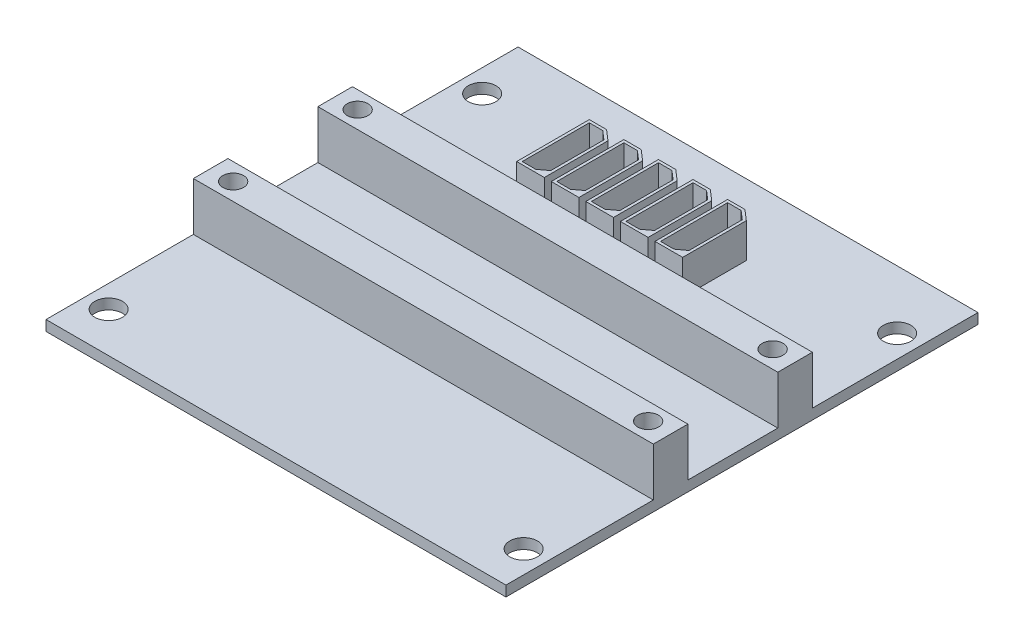
SolidWorks part; units mm, degrees
ref_plane "Front Plane" through (0, 0, 0) normal (0, 0, 1) x (1, 0, 0)
ref_plane "Top Plane" through (0, 0, 0) normal (0, 1, 0) x (1, 0, 0)
ref_plane "Right Plane" through (0, 0, 0) normal (1, 0, 0) x (0, 0, -1)
sketch "Sketch1" plane through (0, 0, 0) normal (0, 1, 0) x (1, 0, 0)
  line L1 (-33.25, 34.125) -> (33.25, 34.125)
  line L2 (-33.25, 34.125) -> (-33.25, -34.125)
  line L3 (-33.25, -34.125) -> (33.25, -34.125)
  line L4 (33.25, 34.125) -> (33.25, -34.125)
  line L5 (-33.25, 34.125) -> (33.25, -34.125) construction
  line L6 (-33.25, -34.125) -> (33.25, 34.125) construction
  point P0 (0, 0)
  dimension "D1" = 68.25
  dimension "D2" = 66.5
extrude "Boss-Extrude1" add sketch "Sketch1" along normal blind 1.5
sketch "Sketch3" plane through (0, 1.5, 0) normal (0, 1, 0) x (1, 0, 0)
  line L2 (0, 34.125) -> (0, -34.125) construction
  line L3 (33.25, 34.125) -> (-33.25, 34.125) construction
  line L4 (-33.25, -34.125) -> (33.25, -34.125) construction
  circle A0 centre (-30, -28.3176) radius 2
  circle A1 centre (30, -28.3176) radius 2
  circle A2 centre (30, 25.6824) radius 2
  circle A3 centre (-30, 25.6824) radius 2
  circle A4 centre (30, 7.6824) radius 1.5
  circle A5 centre (30, -10.3176) radius 1.5
  circle A6 centre (-30, -10.3176) radius 1.5
  circle A7 centre (-30, 7.6824) radius 1.5
  dimension "D7" = 4
  dimension "D8" = 4
  dimension "D9" = 4
  dimension "D10" = 4
  dimension "D14" = 3
  dimension "D15" = 3
  dimension "D1" = 60
  dimension "D2" = 30
  dimension "D3" = 30
  dimension "D4" = 54
  dimension "D5" = 54
  dimension "D6" = 30
  dimension "D11" = 18
  dimension "D12" = 18
  dimension "D13" = 18
extrude "Cut-Extrude1" cut sketch "Sketch3" against normal through all both and the other way through all
sketch "Sketch5" plane through (0, 1.5, 0) normal (0, 1, 0) x (1, 0, 0)
  line L5 (-14.0063, 25.1824) -> (-11.5063, 25.1824)
  line L6 (-11.5063, 25.1824) -> (-10.0063, 23.8824)
  line L8 (-10.0063, 23.8824) -> (-10.0063, 14.6824)
  line L9 (-10.0063, 14.6824) -> (-14.0063, 14.6824)
  line L10 (-14.0063, 14.6824) -> (-14.0063, 25.1824)
  line L11 (-10.4063, 23.6998) -> (-10.4063, 15.9998)
  line L12 (-11.6563, 15.0824) -> (-13.6063, 15.0824)
  line L13 (-13.6063, 15.0824) -> (-13.6063, 24.7824)
  line L14 (-13.6063, 24.7824) -> (-11.6555, 24.7824)
  line L15 (-11.6555, 24.7824) -> (-10.4063, 23.6998)
  line L16 (-10.4063, 15.9998) -> (-11.6563, 15.0824)
  line L17 (-10.4063, 23.6998) -> (-10.4063, 15.0824) construction
  line L18 (-10.4063, 15.0824) -> (-13.6063, 15.0824) construction
  line L19 (-9.0063, 25.1824) -> (-6.5063, 25.1824)
  line L20 (-6.5063, 25.1824) -> (-5.0063, 23.8824)
  line L21 (-5.0063, 23.8824) -> (-5.0063, 14.6824)
  line L22 (-5.0063, 14.6824) -> (-9.0063, 14.6824)
  line L23 (-9.0063, 14.6824) -> (-9.0063, 25.1824)
  line L24 (-5.4063, 23.6998) -> (-5.4063, 15.9998)
  line L25 (-6.6563, 15.0824) -> (-8.6063, 15.0824)
  line L26 (-8.6063, 15.0824) -> (-8.6063, 24.7824)
  line L27 (-8.6063, 24.7824) -> (-6.6555, 24.7824)
  line L28 (-6.6555, 24.7824) -> (-5.4063, 23.6998)
  line L29 (-5.4063, 15.9998) -> (-6.6563, 15.0824)
  line L30 (-4.0063, 25.1824) -> (-1.5063, 25.1824)
  line L31 (-1.5063, 25.1824) -> (-0.0063, 23.8824)
  line L32 (-0.0063, 23.8824) -> (-0.0063, 14.6824)
  line L33 (-0.0063, 14.6824) -> (-4.0063, 14.6824)
  line L34 (-4.0063, 14.6824) -> (-4.0063, 25.1824)
  line L35 (-0.4063, 23.6998) -> (-0.4063, 15.9998)
  line L36 (-1.6563, 15.0824) -> (-3.6063, 15.0824)
  line L37 (-3.6063, 15.0824) -> (-3.6063, 24.7824)
  line L38 (-3.6063, 24.7824) -> (-1.6555, 24.7824)
  line L39 (-1.6555, 24.7824) -> (-0.4063, 23.6998)
  line L40 (-0.4063, 15.9998) -> (-1.6563, 15.0824)
  line L41 (0.9937, 25.1824) -> (3.4937, 25.1824)
  line L42 (3.4937, 25.1824) -> (4.9937, 23.8824)
  line L43 (4.9937, 23.8824) -> (4.9937, 14.6824)
  line L44 (4.9937, 14.6824) -> (0.9937, 14.6824)
  line L45 (0.9937, 14.6824) -> (0.9937, 25.1824)
  line L46 (4.5937, 23.6998) -> (4.5937, 15.9998)
  line L47 (3.3437, 15.0824) -> (1.3937, 15.0824)
  line L48 (1.3937, 15.0824) -> (1.3937, 24.7824)
  line L49 (1.3937, 24.7824) -> (3.3445, 24.7824)
  line L50 (3.3445, 24.7824) -> (4.5937, 23.6998)
  line L51 (4.5937, 15.9998) -> (3.3437, 15.0824)
  line L52 (5.9937, 25.1824) -> (8.4937, 25.1824)
  line L53 (8.4937, 25.1824) -> (9.9937, 23.8824)
  line L54 (9.9937, 23.8824) -> (9.9937, 14.6824)
  line L55 (9.9937, 14.6824) -> (5.9937, 14.6824)
  line L56 (5.9937, 14.6824) -> (5.9937, 25.1824)
  line L57 (9.5937, 23.6998) -> (9.5937, 15.9998)
  line L58 (8.3437, 15.0824) -> (6.3937, 15.0824)
  line L59 (6.3937, 15.0824) -> (6.3937, 24.7824)
  line L60 (6.3937, 24.7824) -> (8.3445, 24.7824)
  line L61 (8.3445, 24.7824) -> (9.5937, 23.6998)
  line L62 (9.5937, 15.9998) -> (8.3437, 15.0824)
  line L63 (-14.0063, 25.1824) -> (-9.0063, 25.1824) construction
  line L64 (-33.25, 14.6824) -> (33.25, 14.6824) construction
  line L65 (-33.25, 34.125) -> (-33.25, -34.125) construction
  line L66 (33.25, -34.125) -> (33.25, 34.125) construction
  circle A0 centre (-30, 7.6824) radius 1.5 construction
  dimension "D1" = 7.7
  dimension "D2" = 10.5
  dimension "D3" = 4
  dimension "D4" = 2.5
  dimension "D6" = 1.95
  dimension "D8" = 5
  dimension "D9" = 7
  dimension "D5" = 0.4
  dimension "D7" = 5
extrude "Boss-Extrude2" add sketch "Sketch5" along normal blind 5
sketch "Sketch6" plane through (0, 1.5, 0) normal (0, 1, 0) x (1, 0, 0)
  line L0 (-33.25, 34.125) -> (-33.25, -34.125) construction
  line L1 (-33.25, 10.1824) -> (33.25, 10.1824)
  line L2 (-33.25, 10.1824) -> (-33.25, 5.1824)
  line L3 (-33.25, 5.1824) -> (33.25, 5.1824)
  line L4 (33.25, 10.1824) -> (33.25, 5.1824)
  line L5 (33.25, -34.125) -> (33.25, 34.125) construction
  line L7 (-33.25, -7.8176) -> (33.25, -7.8176)
  line L8 (-33.25, -7.8176) -> (-33.25, -12.8176)
  line L9 (-33.25, -12.8176) -> (33.25, -12.8176)
  line L10 (33.25, -7.8176) -> (33.25, -12.8176)
  circle A0 centre (-30, 7.6824) radius 1.5 construction
  circle A1 centre (-30, -10.3176) radius 1.5 construction
  dimension "D2" = 2.5
  dimension "D4" = 2.5
  dimension "D1" = 5
  dimension "D3" = 5
extrude "Boss-Extrude3" add sketch "Sketch6" along normal blind 7
sketch "Sketch7" plane through (0, 8.5, 0) normal (0, 1, 0) x (1, 0, 0)
  circle A0 centre (-30, 7.6824) radius 1.5
  circle A1 centre (-30, -10.3176) radius 1.5
  circle A2 centre (30, -10.3176) radius 1.5
  circle A3 centre (30, 7.6824) radius 1.5
  dimension "D1" = 3
  dimension "D2" = 3
  dimension "D3" = 3
  dimension "D4" = 3
extrude "Cut-Extrude2" cut sketch "Sketch7" against normal through all both and the other way through all
